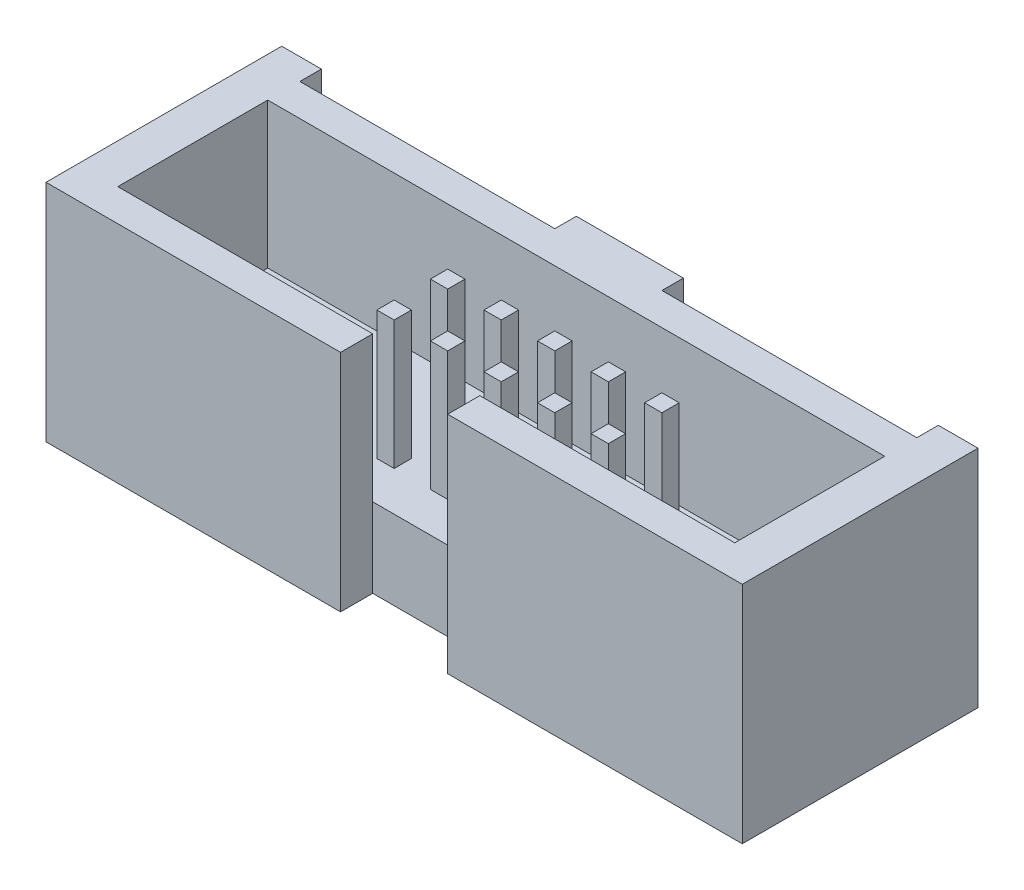
SolidWorks part; units mm, degrees
ref_plane "Front Plane" through (0, 0, 0) normal (0, 0, 1) x (1, 0, 0)
ref_plane "Top Plane" through (0, 0, 0) normal (0, 1, 0) x (1, 0, 0)
ref_plane "Right Plane" through (0, 0, 0) normal (1, 0, 0) x (0, 0, -1)
sketch "Sketch1" plane through (0, 0, 0) normal (0, 1, 0) x (1, 0, 0)
  line L0 (-8.255, -2.54) -> (8.255, -2.54)
  line L1 (-8.255, -2.54) -> (-8.255, 2.54)
  line L2 (8.255, -2.54) -> (8.255, 2.54)
  line L3 (-8.255, 2.54) -> (8.255, 2.54)
  line L4 (-8.255, -2.54) -> (8.255, 2.54) construction
  line L5 (8.255, -2.54) -> (-8.255, 2.54) construction
  point P1 (0, 0)
  dimension "D1" = 5.08
  dimension "D2" = 16.51
extrude "Boss-Extrude1" add sketch "Sketch1" along normal blind 5.33
sketch "Sketch2" plane through (0, 5.33, 0) normal (0, 1, 0) x (1, 0, 0)
  line L0 (-7.315, 1.778) -> (7.315, 1.778)
  line L1 (-7.315, 1.778) -> (-7.315, -1.778)
  line L2 (7.315, 1.778) -> (7.315, -1.778)
  line L3 (-7.315, -1.778) -> (7.315, -1.778)
  line L4 (-7.315, 1.778) -> (7.315, -1.778) construction
  line L5 (7.315, 1.778) -> (-7.315, -1.778) construction
  line L7 (-8.255, 2.54) -> (-8.255, -2.54) construction
  point P1 (0, 0)
  dimension "D1" = 3.556
  dimension "D2" = 0.94
extrude "Cut-Extrude1" cut sketch "Sketch2" against normal blind 3.45
sketch "Sketch4" plane through (0, 0, -2.54) normal (0, 0, -1) x (-1, 0, 0)
  line L0 (-8.255, 0) -> (-8.255, 5.33)
  line L1 (-8.255, 0) -> (-7.315, 0)
  line L2 (-8.255, 5.33) -> (-7.315, 5.33)
  line L3 (-7.315, 0) -> (-7.315, 5.33)
  line L4 (0, 0) -> (0, 5.33)
  line L5 (0, 0) -> (-1.27, 0)
  line L6 (0, 5.33) -> (-1.27, 5.33)
  line L7 (-1.27, 0) -> (-1.27, 5.33)
  line L8 (-8.255, 5.33) -> (8.255, 5.33) construction
  dimension "D1" = 0.94
  dimension "D2" = 1.27
extrude "Boss-Extrude2" add sketch "Sketch4" along normal blind 0.51
sketch "Sketch5" plane through (0, 0, 2.54) normal (0, 0, 1) x (1, 0, 0)
  line L0 (0, 0) -> (0, 5.33)
  line L1 (0, 0) -> (1.27, 0)
  line L2 (0, 5.33) -> (1.27, 5.33)
  line L3 (1.27, 0) -> (1.27, 5.33)
  line L4 (-8.255, 0) -> (8.255, 0) construction
  line L5 (-8.255, 5.33) -> (8.255, 5.33) construction
  dimension "D1" = 1.27
extrude "Cut-Extrude2" cut sketch "Sketch5" against normal up to surface (0.762 mm away) up to face at (0, 3.605, 1.778)
mirror "Mirror1" about plane through (0, 0, 0) normal (1, 0, 0) of "Cut-Extrude2", "Boss-Extrude2", "Cut-Extrude1"
sketch "Sketch6" plane through (0, 1.88, 0) normal (0, 1, 0) x (1, 0, 0)
  line L0 (0.43, -0.84) -> (0.43, -0.43)
  line L1 (0.43, -0.84) -> (0.84, -0.84)
  line L2 (0.43, -0.43) -> (0.84, -0.43)
  line L3 (0.84, -0.84) -> (0.84, -0.43)
  line L4 (0.43, -0.84) -> (0.84, -0.43) construction
  line L5 (0.43, -0.43) -> (0.84, -0.84) construction
  point P1 (0.635, -0.635)
  dimension "D1" = 0.41
  dimension "D2" = 0.41
  dimension "D3" = 0.635
  dimension "D4" = 0.635
extrude "Boss-Extrude3" add sketch "Sketch6" along normal blind 3.05
pattern_linear "LPattern1" count 3 spacing 1.27 along (1, 0, 0) count 3 spacing 1.27 along (-1, 0, 0) of "Boss-Extrude3"
mirror "Mirror2" about plane through (0, 0, 0) normal (0, 0, 1) of "LPattern1", "Boss-Extrude3"
